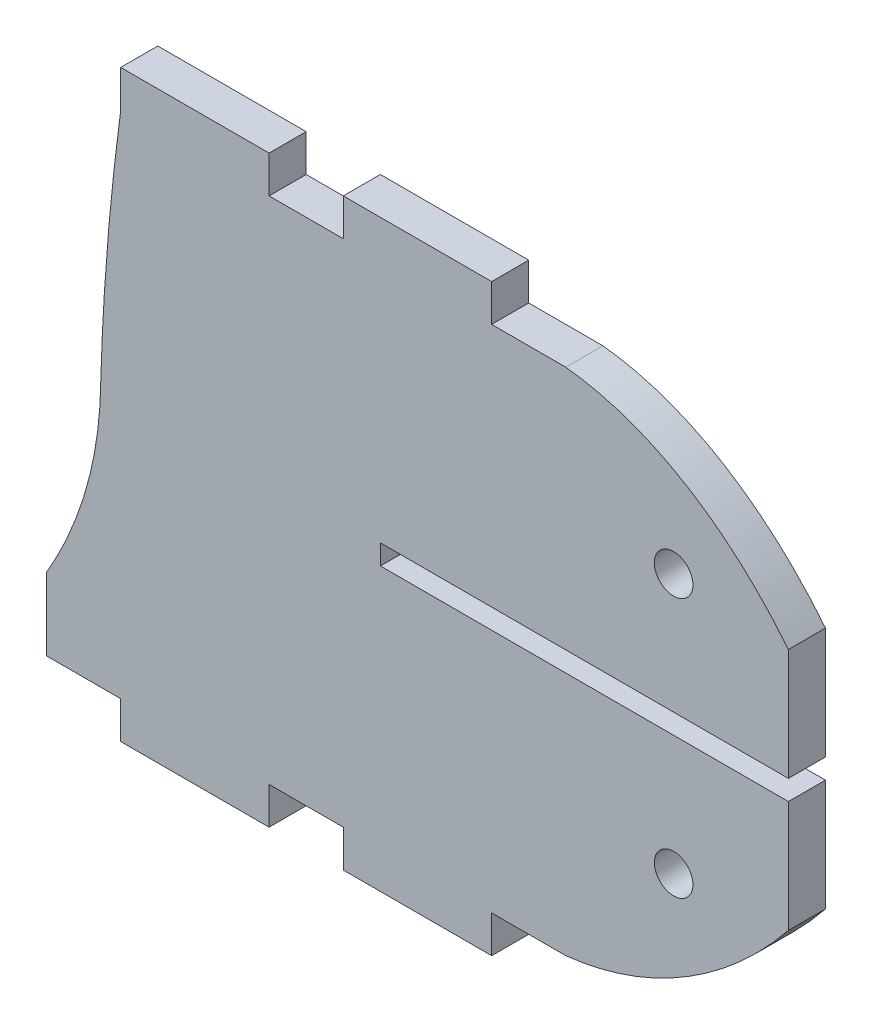
SolidWorks part; units mm, degrees
ref_plane "Front Plane" through (0, 0, 0) normal (0, 0, 1) x (1, 0, 0)
ref_plane "Top Plane" through (0, 0, 0) normal (0, 1, 0) x (1, 0, 0)
ref_plane "Right Plane" through (0, 0, 0) normal (1, 0, 0) x (0, 0, -1)
sketch "Sketch1" plane through (0, 0, 0) normal (0, 0, 1) x (1, 0, 0)
  line L0 (-189.395, -1132.1366) -> (-189.395, -154.5859) construction
  line L1 (-189.032, -128.65) -> (-189.1272, -128.65) construction
  line L2 (-189.395, -95.65) -> (-189.395, 872.3806) construction
  line L4 (-144.395, -128.65) -> (-89.395, -128.65)
  line L6 (-89.395, -146.3973) -> (-89.395, -131.35)
  line L8 (-144.395, -128.65) -> (-189.395, -128.65) construction
  line L10 (-189.395, -131.35) -> (-144.395, -131.35) construction
  line L11 (-144.395, -131.35) -> (-144.395, -128.65)
  line L12 (-189.395, -164.35) -> (-189.395, -154.5859)
  line L13 (-144.395, -131.35) -> (-89.395, -131.35)
  line L14 (-89.395, -128.65) -> (-89.395, -113.6027)
  line L15 (-144.395, -130) -> (-156.5226, -130) construction
  line L16 (-129.395, -95.65) -> (-129.395, -90.65)
  line L18 (-179.395, -95.65) -> (-179.395, -90.65)
  line L19 (-179.395, -90.65) -> (-159.395, -90.65)
  line L20 (-159.395, -95.65) -> (-159.395, -90.65)
  line L21 (-149.395, -90.65) -> (-129.395, -90.65)
  line L22 (-149.395, -95.65) -> (-149.395, -90.65)
  line L27 (-149.395, -95.65) -> (-159.395, -95.65)
  line L28 (-119.395, -95.65) -> (-129.395, -95.65)
  line L29 (-119.395, -164.35) -> (-129.395, -164.35)
  line L30 (-149.395, -164.35) -> (-159.395, -164.35)
  line L34 (-149.395, -164.35) -> (-149.395, -169.35)
  line L35 (-149.395, -169.35) -> (-129.395, -169.35)
  line L36 (-159.395, -164.35) -> (-159.395, -169.35)
  line L37 (-179.395, -169.35) -> (-159.395, -169.35)
  line L38 (-179.395, -164.35) -> (-179.395, -169.35)
  line L39 (-129.395, -164.35) -> (-129.395, -169.35)
  line L40 (-179.395, -164.35) -> (-189.395, -164.35)
  line L41 (-149.395, -164.35) -> (-159.395, -164.35)
  line L42 (-119.395, -164.35) -> (-129.395, -164.35)
  line L43 (-99.395, -95.65) -> (-99.395, -90.65) [skipped]
  line L44 (-119.395, -90.65) -> (-117.2805, -90.65) [skipped]
  line L45 (-119.395, -95.65) -> (-119.395, -90.65) [skipped]
  circle A1 centre (-104.8604, -112.5) radius 2.6
  circle A2 centre (-104.8604, -147.5) radius 2.6
  spline S0 degree 3 poles (-89.395, -113.6027) (-96.8318, -104.3449) (-107.1665, -96.9975) (-119.395, -95.65) knots 0 0 0 0 1 1 1 1
  spline S1 degree 3 poles (-89.395, -146.3973) (-96.8318, -155.6551) (-107.1665, -163.0025) (-119.395, -164.35) knots 0 0 0 0 1 1 1 1
  spline S2 degree 2 poles (-179.395, -95.65) (-181.601, -112.0746) (-182.0845, -128.65) knots 0 0 0 1 1 1
  spline S3 degree 2 poles (-182.0845, -128.65) (-182.2427, -142.3221) (-189.395, -154.5859) knots 0 0 0 1 1 1
  point P2 (-144.395, -130)
  dimension "D1" = 5.2
  dimension "D3" = 45
  dimension "D4" = 2.7
  dimension "D7" = 20
  dimension "D8" = 3
extrude "Boss-Extrude1" add sketch "Sketch1" along normal blind 5
